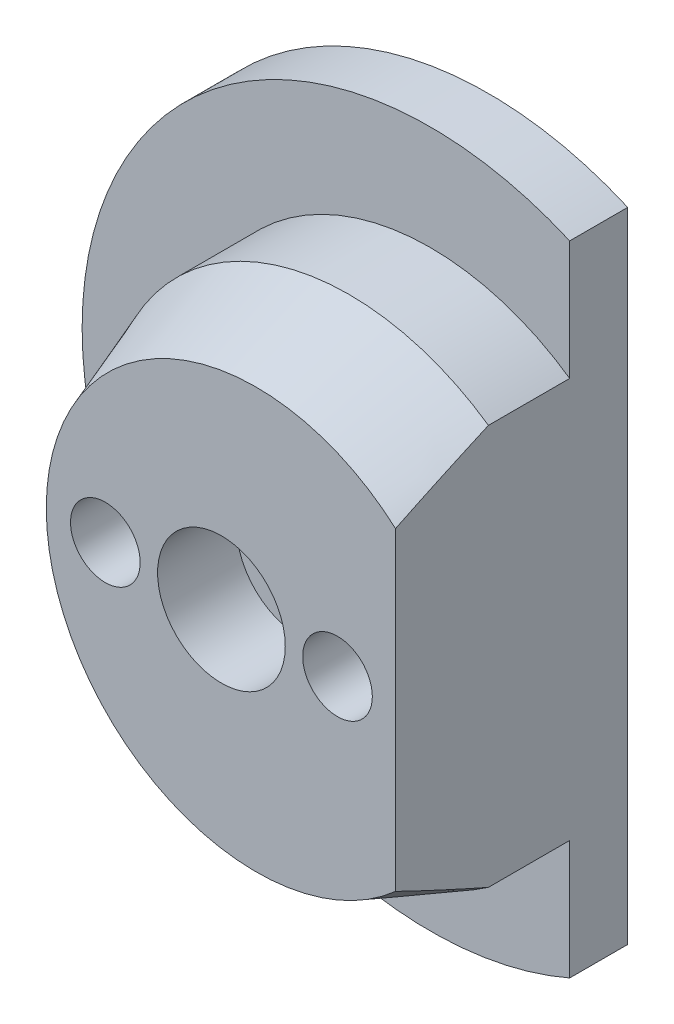
SolidWorks part; units mm, degrees
material "Q235A"
ref_plane "前视" through (0, 0, 0) normal (0, 0, 1) x (1, 0, 0)
ref_plane "上视" through (0, 0, 0) normal (0, 1, 0) x (1, 0, 0)
ref_plane "右视" through (0, 0, 0) normal (1, 0, 0) x (0, 0, -1)
sketch "草图1" plane through (0, 0, 0) normal (0, 0, 1) x (1, 0, 0)
  circle A0 centre (0, 0) radius 30
  dimension "D1" = 60
extrude "凸台-拉伸1" add sketch "草图1" along normal blind 20
hole_wizard "大小mm 暗销孔1" positions "草图3" profile "草图2" hole size "Ø6.0" standard "GB"
sketch "草图3" plane through (0, 0, 20) normal (0, 0, 1) x (1, 0, 0)
  line L0 (50, 0) -> (-50, 0) construction
  line L1 (0, -50) -> (0, 50) construction
  point P0 (-13, 0)
  point P4 (7, 0)
  dimension "D1" = 20
  dimension "D2" = 13
sketch "草图2" plane through (-13, 0, 20) normal (1, 0, 0) x (0, -1, 0)
  line L0 (0, 0) -> (0, 21.8026)
  line L1 (0, 21.8026) -> (3, 20)
  line L2 (3, 20) -> (3, 0)
  line L5 (3, 0) -> (0, 0)
  line L10 (0, 21.8026) -> (-3, 20) construction
  line L11 (0, -6.35) -> (0, 107.95) construction
  dimension "孔直径" = 6
  dimension "孔深度" = 20
  dimension "导头角度" = 118
hole_wizard "打孔尺寸(%根据)内六角圆柱头螺钉的类型1" positions "草图5" profile "草图4" counterbore size "M6" standard "GB"
sketch "草图5" plane through (0, 0, 20) normal (0, 0, 1) x (1, 0, 0)
  line L0 (50, 0) -> (-50, 0) construction
  circle A0 centre (-13, 0) radius 3 construction
  point P0 (-3, 0)
  dimension "D1" = 10
sketch "草图4" plane through (-3, 0, 20) normal (1, 0, 0) x (0, -1, 0)
  line L0 (0, 0) -> (0, 21.9828)
  line L1 (0, 21.9828) -> (3.3, 20)
  line L2 (3.3, 20) -> (3.3, 6.8)
  line L3 (3.3, 6.8) -> (5.5, 6.8)
  line L4 (5.5, 6.8) -> (5.5, 0)
  line L5 (5.5, 0) -> (0, 0)
  line L10 (0, 21.9828) -> (-3.3, 20) construction
  line L11 (0, -6.35) -> (0, 107.95) construction
  dimension "孔直径" = 6.6
  dimension "孔深度" = 20
  dimension "柱形沉头孔直径" = 11
  dimension "柱形沉头孔深度" = 6.8
  dimension "导头角度" = 118
sketch "草图6" plane through (0, 0, 20) normal (0, 0, 1) x (1, 0, 0)
  circle A0 centre (0, 0) radius 21
  dimension "D1" = 42
extrude "切除-拉伸1" cut sketch "草图6" against normal blind 15 flip side to cut
chamfer "倒角1" distance 8 angle 20 1 edges at (21, 0, 20)
sketch "草图7" plane through (0, 0, 20) normal (0, 0, 1) x (1, 0, 0)
  line L1 (12, 33.1106) -> (47.9723, 33.1106)
  line L2 (12, 33.1106) -> (12, -35.2958)
  line L3 (12, -35.2958) -> (47.9723, -35.2958)
  line L4 (47.9723, 33.1106) -> (47.9723, -35.2958)
  dimension "D1" = 12
extrude "切除-拉伸2" cut sketch "草图7" against normal through all
